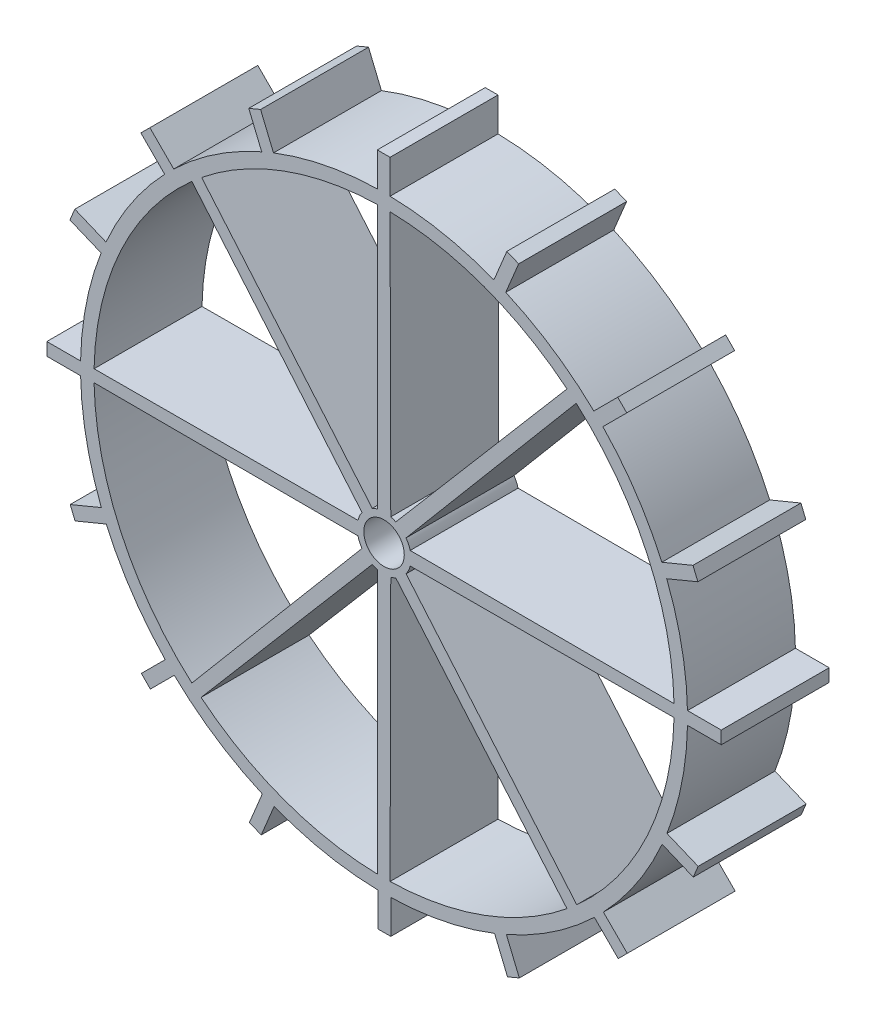
SolidWorks part; units mm, degrees
ref_plane "Alzado" through (0, 0, 0) normal (0, 0, 1) x (1, 0, 0)
ref_plane "Planta" through (0, 0, 0) normal (0, 1, 0) x (1, 0, 0)
ref_plane "Vista lateral" through (0, 0, 0) normal (1, 0, 0) x (0, 0, -1)
sketch "Croquis1" plane through (0, 0, 0) normal (0, 0, 1) x (1, 0, 0)
  line L4 (-142.488, 161.0732) -> (-12.9607, 7.5511)
  line L5 (4.479, -215.0054) -> (5, -14.1421)
  line L6 (-135.6563, -166.8675) -> (-5.3344, -14.0194)
  line L7 (-225.0054, -4.4531) -> (-224.9559, -4.4532)
  line L8 (-151.4262, 186.2662) -> (-5.3344, 14.0194)
  line L9 (-5, -240) -> (-5, -14.1421)
  line L10 (-142.488, -161.0732) -> (-12.9607, -7.5511)
  line L11 (-225.0054, 4.4531) -> (-224.9559, 4.4532)
  line L12 (5.6201, 224.9298) -> (5.7499, 274.9929)
  line L15 (-5, 224.9444) -> (-5, 250)
  line L17 (141.2055, 175.1742) -> (173.4888, 213.438)
  line L20 (149.7776, 167.9038) -> (182.259, 205.9996)
  line L22 (224.9298, 5.6201) -> (274.9929, 5.7499)
  line L25 (224.9298, -5.6201) -> (274.9929, -5.7499)
  line L27 (149.3142, -168.316) -> (165.5209, -187.4242)
  line L30 (141.2055, -175.1742) -> (173.4888, -213.438)
  line L32 (-214.9533, 4.4792) -> (-14.1421, 5)
  line L33 (-214.9533, -4.4792) -> (-14.1421, -5)
  line L40 (12.9607, -7.5511) -> (142.8442, -160.6877)
  line L44 (14.1421, 5) -> (214.9533, 4.4792)
  line L45 (12.9607, 7.5511) -> (142.4544, 161.0334)
  line L47 (5, 14.1421) -> (4.4792, 214.9533)
  line L48 (5.3344, 14.0194) -> (135.6225, 166.8279)
  line L50 (-5, 14.1421) -> (-5, 214.9419)
  line L61 (5.3344, -14.0194) -> (135.6225, -166.8279)
  line L64 (14.1421, -5) -> (214.9533, -4.4792)
  circle A0 centre (0, 0) radius 225
  arc A1 (135.6225, 166.8279) -> (4.4792, 214.9533) centre (0, 0) ccw
  arc A2 (-5, 14.1421) -> (-5.3344, 14.0194) centre (0, 0) ccw
  arc A3 (5.3344, 14.0194) -> (5, 14.1421) centre (0, 0) ccw
  arc A4 (14.1421, 5) -> (12.9607, 7.5511) centre (0, 0) ccw
  arc A5 (12.9607, -7.5511) -> (14.1421, -5) centre (0, 0) ccw
  arc A6 (5, -14.1421) -> (5.3344, -14.0194) centre (0, 0) ccw
  arc A7 (-5.3344, -14.0194) -> (-5, -14.1421) centre (0, 0) ccw
  arc A8 (-14.1421, -5) -> (-12.9607, -7.5511) centre (0, 0) ccw
  arc A9 (-12.9607, 7.5511) -> (-14.1421, 5) centre (0, 0) ccw
  circle A10 centre (0, 0) radius 215 construction
  arc A11 (-5, 214.9419) -> (-135.2178, 167.156) centre (0, 0) ccw
  arc A12 (-142.4544, 161.0334) -> (-214.9533, 4.4792) centre (0, 0) ccw
  arc A13 (-214.9533, -4.4792) -> (-142.4544, -161.0334) centre (0, 0) ccw
  arc A14 (-135.6225, -166.8279) -> (-5, -214.9419) centre (0, 0) ccw
  arc A15 (4.4792, -214.9533) -> (135.6225, -166.8279) centre (0, 0) ccw
  arc A16 (142.8442, -160.6877) -> (214.9533, -4.4792) centre (0, 0) ccw
  arc A17 (214.9533, 4.4792) -> (142.4544, 161.0334) centre (0, 0) ccw
  point P6 (0, 0)
  point P9 (0, 0)
  point P12 (0, 0)
  point P15 (0, 0)
  dimension "D1" = 450
  dimension "D5" = 30
  dimension "D2" = 10
extrude "Saliente-Extruir1" add sketch "Croquis1" along normal mid plane 80
sketch "Croquis2" plane through (0, 0, 40) normal (0, 0, 1) x (1, 0, 0)
  line L0 (90.2249, 206.1176) -> (99.792, 229.2146)
  line L1 (4.4792, 224.9554) -> (-5, 224.9554)
  line L2 (4.4792, 224.9554) -> (4.4792, 249.9554)
  line L3 (4.4792, 249.9554) -> (-5, 249.9554)
  line L4 (-5, 224.9554) -> (-5, 249.9554)
  line L5 (90.2249, 206.1176) -> (81.4673, 209.7451)
  line L6 (81.4673, 209.7451) -> (91.0344, 232.8421)
  line L7 (99.792, 229.2146) -> (91.0344, 232.8421)
  line L8 (162.2347, 155.9002) -> (179.9124, 173.5779)
  line L9 (162.2347, 155.9002) -> (155.532, 162.603)
  line L10 (155.532, 162.603) -> (173.2096, 180.2807)
  line L11 (179.9124, 173.5779) -> (173.2096, 180.2807)
  line L12 (209.5458, 81.9485) -> (232.6428, 91.5156)
  line L13 (209.5458, 81.9485) -> (205.9183, 90.7061)
  line L14 (205.9183, 90.7061) -> (229.0153, 100.2732)
  line L15 (232.6428, 91.5156) -> (229.0153, 100.2732)
  line L16 (224.9554, -4.4792) -> (249.9554, -4.4792)
  line L17 (224.9554, -4.4792) -> (224.9554, 5)
  line L18 (224.9554, 5) -> (249.9554, 5)
  line L19 (249.9554, -4.4792) -> (249.9554, 5)
  line L20 (206.1176, -90.2249) -> (229.2146, -99.792)
  line L21 (206.1176, -90.2249) -> (209.7451, -81.4673)
  line L22 (209.7451, -81.4673) -> (232.8421, -91.0344)
  line L23 (229.2146, -99.792) -> (232.8421, -91.0344)
  line L24 (155.9002, -162.2347) -> (173.5779, -179.9124)
  line L25 (155.9002, -162.2347) -> (162.603, -155.532)
  line L26 (162.603, -155.532) -> (180.2807, -173.2096)
  line L27 (173.5779, -179.9124) -> (180.2807, -173.2096)
  line L28 (81.9485, -209.5458) -> (91.5156, -232.6428)
  line L29 (81.9485, -209.5458) -> (90.7061, -205.9183)
  line L30 (90.7061, -205.9183) -> (100.2732, -229.0153)
  line L31 (91.5156, -232.6428) -> (100.2732, -229.0153)
  line L32 (-4.4792, -224.9554) -> (-4.4792, -249.9554)
  line L33 (-4.4792, -224.9554) -> (5, -224.9554)
  line L34 (5, -224.9554) -> (5, -249.9554)
  line L35 (-4.4792, -249.9554) -> (5, -249.9554)
  line L36 (-90.2249, -206.1176) -> (-99.792, -229.2146)
  line L37 (-90.2249, -206.1176) -> (-81.4673, -209.7451)
  line L38 (-81.4673, -209.7451) -> (-91.0344, -232.8421)
  line L39 (-99.792, -229.2146) -> (-91.0344, -232.8421)
  line L40 (-162.2347, -155.9002) -> (-179.9124, -173.5779)
  line L41 (-162.2347, -155.9002) -> (-155.532, -162.603)
  line L42 (-155.532, -162.603) -> (-173.2096, -180.2807)
  line L43 (-179.9124, -173.5779) -> (-173.2096, -180.2807)
  line L44 (-209.5458, -81.9485) -> (-232.6428, -91.5156)
  line L45 (-209.5458, -81.9485) -> (-205.9183, -90.7061)
  line L46 (-205.9183, -90.7061) -> (-229.0153, -100.2732)
  line L47 (-232.6428, -91.5156) -> (-229.0153, -100.2732)
  line L48 (-224.9554, 4.4792) -> (-249.9554, 4.4792)
  line L49 (-224.9554, 4.4792) -> (-224.9554, -5)
  line L50 (-224.9554, -5) -> (-249.9554, -5)
  line L51 (-249.9554, 4.4792) -> (-249.9554, -5)
  line L52 (-206.1176, 90.2249) -> (-229.2146, 99.792)
  line L53 (-206.1176, 90.2249) -> (-209.7451, 81.4673)
  line L54 (-209.7451, 81.4673) -> (-232.8421, 91.0344)
  line L55 (-229.2146, 99.792) -> (-232.8421, 91.0344)
  line L56 (-155.9002, 162.2347) -> (-173.5779, 179.9124)
  line L57 (-155.9002, 162.2347) -> (-162.603, 155.532)
  line L58 (-162.603, 155.532) -> (-180.2807, 173.2096)
  line L59 (-173.5779, 179.9124) -> (-180.2807, 173.2096)
  line L60 (-81.9485, 209.5458) -> (-91.5156, 232.6428)
  line L61 (-81.9485, 209.5458) -> (-90.7061, 205.9183)
  line L62 (-90.7061, 205.9183) -> (-100.2732, 229.0153)
  line L63 (-91.5156, 232.6428) -> (-100.2732, 229.0153)
  circle A0 centre (0, 0) radius 225 construction
  point P69 (0, 0)
  dimension "D1" = 25
  dimension "D2" = 16
extrude "Saliente-Extruir2" add sketch "Croquis2" against normal up to surface (80 mm away) up to face at (38.6135, -105.223, -40)
sketch "Croquis3" plane through (0, 0, -40) normal (0, 0, -1) x (-1, 0, 0)
  circle A0 centre (0, 0) radius 20
  circle A1 centre (0, 0) radius 15
  dimension "D1" = 40
extrude "Saliente-Extruir3" add sketch "Croquis3" against normal up to surface (80 mm away) contours A0 up to face at (0, 0, 40)
sketch "Croquis4" plane through (0, 0, -40) normal (0, 0, -1) x (-1, 0, 0)
  circle A0 centre (0, 0) radius 15
  dimension "D1" = 30
extrude "Cortar-Extruir1" cut sketch "Croquis4" against normal up to surface (80 mm away) up to face at (39.4663, 107.5469, 40)
sketch "Croquis8" plane through (0, 0, -40) normal (0, 0, -1) x (-1, 0, 0)
  line L0 (0, 0) -> (0, 15) construction
  line L2 (-2, 13.5) -> (2, 13.5)
  line L3 (-2, 13.5) -> (-2, 16.5)
  line L4 (-2, 16.5) -> (2, 16.5)
  line L5 (2, 13.5) -> (2, 16.5)
  line L6 (-2, 13.5) -> (2, 16.5) construction
  line L7 (-2, 16.5) -> (2, 13.5) construction
  circle A0 centre (0, 0) radius 15 construction
  dimension "D1" = 4
  dimension "D2" = 3
extrude "Saliente-Extruir4" add sketch "Croquis8" along normal blind 19
sketch "Croquis9" plane through (0, 0, -40) normal (0, 0, -1) x (-1, 0, 0)
  circle A0 centre (0, 0) radius 15
extrude "Cortar-Extruir3" cut sketch "Croquis9" along normal through all
